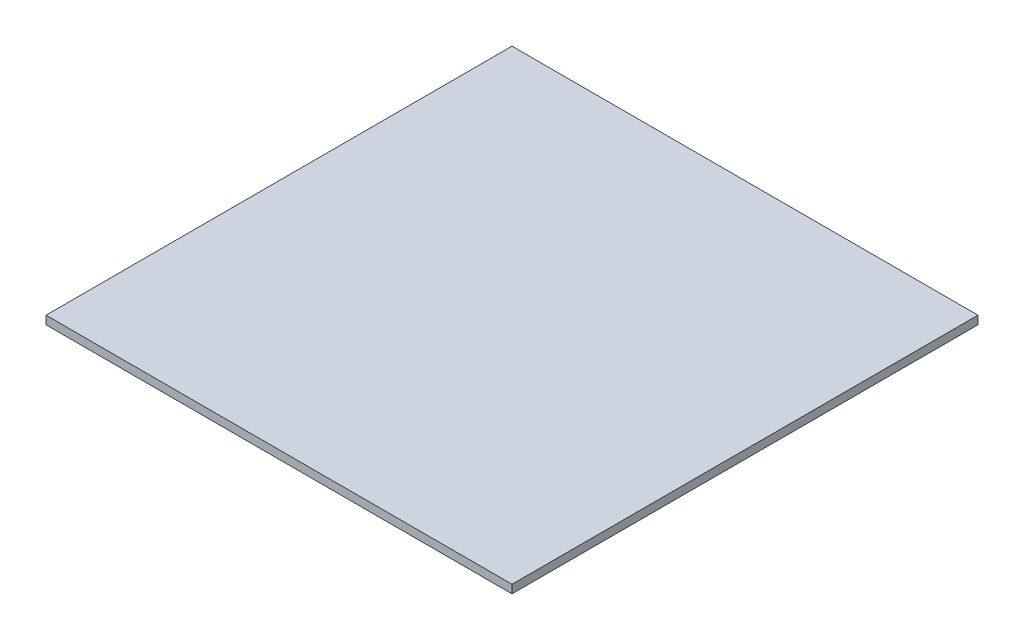
SolidWorks part; units mm, degrees
ref_plane "Front Plane" through (0, 0, 0) normal (0, 0, 1) x (1, 0, 0)
ref_plane "Top Plane" through (0, 0, 0) normal (0, 1, 0) x (1, 0, 0)
ref_plane "Right Plane" through (0, 0, 0) normal (1, 0, 0) x (0, 0, -1)
sketch "Sketch1" plane through (0, 0, 0) normal (0, 1, 0) x (1, 0, 0)
  line L1 (-280, -280) -> (280, -280)
  line L2 (-280, -280) -> (-280, 280)
  line L3 (-280, 280) -> (280, 280)
  line L4 (280, -280) -> (280, 280)
  line L5 (-280, -280) -> (280, 280) construction
  line L6 (-280, 280) -> (280, -280) construction
  point P0 (0, 0)
  dimension "D1" = 560
  dimension "D2" = 560
extrude "Boss-Extrude1" add sketch "Sketch1" along normal blind 10
